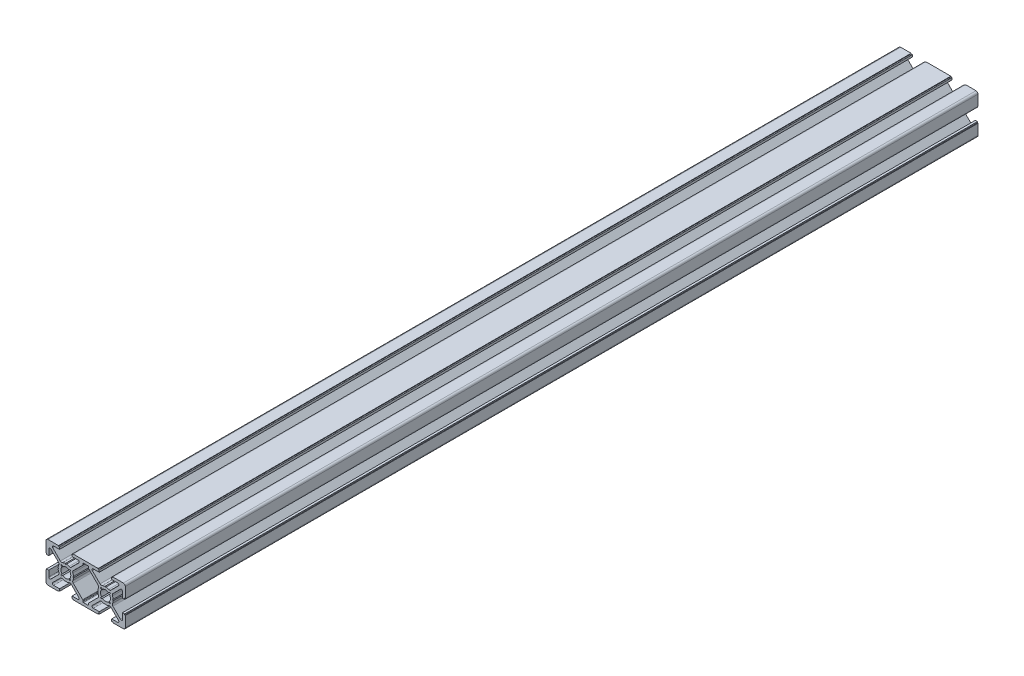
SolidWorks part; units mm, degrees
ref_plane "Front Plane" through (0, 0, 0) normal (0, 0, 1) x (1, 0, 0)
ref_plane "Top Plane" through (0, 0, 0) normal (0, 1, 0) x (1, 0, 0)
ref_plane "Right Plane" through (0, 0, 0) normal (1, 0, 0) x (0, 0, -1)
sketch "Sketch1" plane through (0, 0, 0) normal (0, 0, 1) x (1, 0, 0)
  line B0 (1.9671, 1.5429) -> (2.3335, 1.9092)
  line B1 (1.9092, 2.3335) -> (1.5429, 1.9671)
  line B2 (2.3335, -1.9092) -> (1.9671, -1.5429)
  line B3 (1.5429, -1.9671) -> (1.9092, -2.3335)
  line B4 (-1.9092, -2.3335) -> (-1.5429, -1.9671)
  line B5 (-1.9671, -1.5429) -> (-2.3335, -1.9092)
  line B6 (-2.3335, 1.9092) -> (-1.9671, 1.5429)
  line B7 (-1.5429, 1.9671) -> (-1.9092, 2.3335)
  line B8 (-17.6665, -1.9092) -> (-18.0329, -1.5429)
  line B9 (-18.4571, -1.9671) -> (-18.0908, -2.3335)
  line B10 (-21.9092, -2.3335) -> (-21.5429, -1.9671)
  line B11 (-21.9671, -1.5429) -> (-22.3335, -1.9092)
  line B12 (-18.0329, 1.5429) -> (-17.6665, 1.9092)
  line B13 (-18.0908, 2.3335) -> (-18.4571, 1.9671)
  line B14 (-21.5429, 1.9671) -> (-21.9092, 2.3335)
  line B15 (-22.3335, 1.9092) -> (-21.9671, 1.5429)
  line B16 (-16.1107, 0.2893) -> (-16.4, 0)
  line B17 (-16.4, 0) -> (-16.1107, -0.2893)
  line B18 (-16.2554, -2.7546) -> (-11.4879, -7.5222)
  line B19 (-11.4, -7.7343) -> (-11.4, -8.3)
  line B20 (-11.1, -8.6) -> (-8.9, -8.6)
  line B21 (-8.6, -8.3) -> (-8.6, -7.7343)
  line B22 (-8.5121, -7.5222) -> (-3.7446, -2.7546)
  line B23 (-3.8893, -0.2893) -> (-3.6, 0)
  line B24 (-3.6, 0) -> (-3.8893, 0.2893)
  line B25 (-3.7446, 2.7546) -> (-8.5121, 7.5222)
  line B26 (-8.6, 7.7343) -> (-8.6, 8.3)
  line B27 (-8.9, 8.6) -> (-11.1, 8.6)
  line B28 (-11.4, 8.3) -> (-11.4, 7.7343)
  line B29 (-11.4879, 7.5222) -> (-16.2554, 2.7546)
  line B30 (-30, -3.7) -> (-30, -9)
  line B31 (-29, -10) -> (-23.7, -10)
  line B32 (-23.7, -10) -> (-23.7, -9.7)
  line B33 (-23.7, -9.7) -> (-23.15, -9.7)
  line B34 (-23.15, -9.7) -> (-23.15, -8.6)
  line B35 (-23.15, -8.6) -> (-26.1615, -8.6)
  line B36 (-26.5858, -7.5757) -> (-22.7546, -3.7446)
  line B37 (-20.2893, -3.8893) -> (-20, -3.6)
  line B38 (-20, -3.6) -> (-19.7107, -3.8893)
  line B39 (-17.2454, -3.7446) -> (-13.4142, -7.5757)
  line B40 (-13.8385, -8.6) -> (-16.85, -8.6)
  line B41 (-16.85, -8.6) -> (-16.85, -9.7)
  line B42 (-16.85, -9.7) -> (-16.3, -9.7)
  line B43 (-16.3, -9.7) -> (-16.3, -10)
  line B44 (-16.3, -10) -> (-3.7, -10)
  line B45 (-3.7, -10) -> (-3.7, -9.7)
  line B46 (-3.7, -9.7) -> (-3.15, -9.7)
  line B47 (-3.15, -9.7) -> (-3.15, -8.6)
  line B48 (-3.15, -8.6) -> (-6.1615, -8.6)
  line B49 (-6.5858, -7.5757) -> (-2.7546, -3.7446)
  line B50 (-0.2893, -3.8893) -> (0, -3.6)
  line B51 (0, -3.6) -> (0.2893, -3.8893)
  line B52 (2.7546, -3.7446) -> (6.5858, -7.5757)
  line B53 (6.1615, -8.6) -> (3.15, -8.6)
  line B54 (3.15, -8.6) -> (3.15, -9.7)
  line B55 (3.15, -9.7) -> (3.7, -9.7)
  line B56 (3.7, -9.7) -> (3.7, -10)
  line B57 (3.7, -10) -> (9, -10)
  line B58 (10, -9) -> (10, -3.7)
  line B59 (10, -3.7) -> (9.7, -3.7)
  line B60 (9.7, -3.7) -> (9.7, -3.15)
  line B61 (9.7, -3.15) -> (8.6, -3.15)
  line B62 (8.6, -3.15) -> (8.6, -6.1615)
  line B63 (7.5757, -6.5858) -> (3.7446, -2.7546)
  line B64 (3.8893, -0.2893) -> (3.6, 0)
  line B65 (3.6, 0) -> (3.8893, 0.2893)
  line B66 (3.7446, 2.7546) -> (7.5757, 6.5858)
  line B67 (8.6, 6.1615) -> (8.6, 3.15)
  line B68 (8.6, 3.15) -> (9.7, 3.15)
  line B69 (9.7, 3.15) -> (9.7, 3.7)
  line B70 (9.7, 3.7) -> (10, 3.7)
  line B71 (10, 3.7) -> (10, 9)
  line B72 (9, 10) -> (3.7, 10)
  line B73 (3.7, 10) -> (3.7, 9.7)
  line B74 (3.7, 9.7) -> (3.15, 9.7)
  line B75 (3.15, 9.7) -> (3.15, 8.6)
  line B76 (3.15, 8.6) -> (6.1615, 8.6)
  line B77 (6.5858, 7.5757) -> (2.7546, 3.7446)
  line B78 (0.2893, 3.8893) -> (0, 3.6)
  line B79 (0, 3.6) -> (-0.2893, 3.8893)
  line B80 (-2.7546, 3.7446) -> (-6.5858, 7.5757)
  line B81 (-6.1615, 8.6) -> (-3.15, 8.6)
  line B82 (-3.15, 8.6) -> (-3.15, 9.7)
  line B83 (-3.15, 9.7) -> (-3.7, 9.7)
  line B84 (-3.7, 9.7) -> (-3.7, 10)
  line B85 (-3.7, 10) -> (-16.3, 10)
  line B86 (-16.3, 10) -> (-16.3, 9.7)
  line B87 (-16.3, 9.7) -> (-16.85, 9.7)
  line B88 (-16.85, 9.7) -> (-16.85, 8.6)
  line B89 (-16.85, 8.6) -> (-13.8385, 8.6)
  line B90 (-13.4142, 7.5757) -> (-17.2454, 3.7446)
  line B91 (-19.7107, 3.8893) -> (-20, 3.6)
  line B92 (-20, 3.6) -> (-20.2893, 3.8893)
  line B93 (-22.7546, 3.7446) -> (-26.5858, 7.5757)
  line B94 (-26.1615, 8.6) -> (-23.15, 8.6)
  line B95 (-23.15, 8.6) -> (-23.15, 9.7)
  line B96 (-23.15, 9.7) -> (-23.7, 9.7)
  line B97 (-23.7, 9.7) -> (-23.7, 10)
  line B98 (-23.7, 10) -> (-29, 10)
  line B99 (-30, 9) -> (-30, 3.7)
  line B100 (-30, 3.7) -> (-29.7, 3.7)
  line B101 (-29.7, 3.7) -> (-29.7, 3.15)
  line B102 (-29.7, 3.15) -> (-28.6, 3.15)
  line B103 (-28.6, 3.15) -> (-28.6, 6.1615)
  line B104 (-27.5757, 6.5858) -> (-23.7446, 2.7546)
  line B105 (-23.8893, 0.2893) -> (-23.6, 0)
  line B106 (-23.6, 0) -> (-23.8893, -0.2893)
  line B107 (-23.7446, -2.7546) -> (-27.5757, -6.5858)
  line B108 (-28.6, -6.1615) -> (-28.6, -3.15)
  line B109 (-28.6, -3.15) -> (-29.7, -3.15)
  line B110 (-29.7, -3.15) -> (-29.7, -3.7)
  line B111 (-29.7, -3.7) -> (-30, -3.7)
  arc B112 (1.9671, -1.5429) -> (1.9671, 1.5429) centre (0, 0) ccw
  arc B113 (2.3335, 1.9092) -> (1.9092, 2.3335) centre (2.1213, 2.1213) ccw
  arc B114 (1.5429, 1.9671) -> (-1.5429, 1.9671) centre (0, 0) ccw
  arc B115 (1.9092, -2.3335) -> (2.3335, -1.9092) centre (2.1213, -2.1213) ccw
  arc B116 (-1.5429, -1.9671) -> (1.5429, -1.9671) centre (0, 0) ccw
  arc B117 (-2.3335, -1.9092) -> (-1.9092, -2.3335) centre (-2.1213, -2.1213) ccw
  arc B118 (-1.9671, 1.5429) -> (-1.9671, -1.5429) centre (0, 0) ccw
  arc B119 (-1.9092, 2.3335) -> (-2.3335, 1.9092) centre (-2.1213, 2.1213) ccw
  arc B120 (-18.0908, -2.3335) -> (-17.6665, -1.9092) centre (-17.8787, -2.1213) ccw
  arc B121 (-21.5429, -1.9671) -> (-18.4571, -1.9671) centre (-20, 0) ccw
  arc B122 (-22.3335, -1.9092) -> (-21.9092, -2.3335) centre (-22.1213, -2.1213) ccw
  arc B123 (-21.9671, 1.5429) -> (-21.9671, -1.5429) centre (-20, 0) ccw
  arc B124 (-18.0329, -1.5429) -> (-18.0329, 1.5429) centre (-20, 0) ccw
  arc B125 (-17.6665, 1.9092) -> (-18.0908, 2.3335) centre (-17.8787, 2.1213) ccw
  arc B126 (-18.4571, 1.9671) -> (-21.5429, 1.9671) centre (-20, 0) ccw
  arc B127 (-21.9092, 2.3335) -> (-22.3335, 1.9092) centre (-22.1213, 2.1213) ccw
  arc B128 (-30, -9) -> (-29, -10) centre (-29, -9) ccw
  arc B129 (-26.5858, -7.5757) -> (-26.1615, -8.6) centre (-26.1615, -8) ccw
  arc B130 (-21.6297, -3.5432) -> (-22.7546, -3.7446) centre (-22.0475, -4.4517) ccw
  arc B131 (-21.6297, -3.5432) -> (-20.2893, -3.8893) centre (-20, 0) ccw
  arc B132 (-19.7107, -3.8893) -> (-18.3703, -3.5432) centre (-20, 0) ccw
  arc B133 (-17.2454, -3.7446) -> (-18.3703, -3.5432) centre (-17.9525, -4.4517) ccw
  arc B134 (-13.8385, -8.6) -> (-13.4142, -7.5757) centre (-13.8385, -8) ccw
  arc B135 (-6.5858, -7.5757) -> (-6.1615, -8.6) centre (-6.1615, -8) ccw
  arc B136 (-1.6297, -3.5432) -> (-2.7546, -3.7446) centre (-2.0475, -4.4517) ccw
  arc B137 (-1.6297, -3.5432) -> (-0.2893, -3.8893) centre (0, 0) ccw
  arc B138 (0.2893, -3.8893) -> (1.6297, -3.5432) centre (0, 0) ccw
  arc B139 (2.7546, -3.7446) -> (1.6297, -3.5432) centre (2.0475, -4.4517) ccw
  arc B140 (6.1615, -8.6) -> (6.5858, -7.5757) centre (6.1615, -8) ccw
  arc B141 (9, -10) -> (10, -9) centre (9, -9) ccw
  arc B142 (7.5757, -6.5858) -> (8.6, -6.1615) centre (8, -6.1615) ccw
  arc B143 (3.5432, -1.6297) -> (3.7446, -2.7546) centre (4.4517, -2.0475) ccw
  arc B144 (3.5432, -1.6297) -> (3.8893, -0.2893) centre (0, 0) ccw
  arc B145 (3.8893, 0.2893) -> (3.5432, 1.6297) centre (0, 0) ccw
  arc B146 (3.7446, 2.7546) -> (3.5432, 1.6297) centre (4.4517, 2.0475) ccw
  arc B147 (8.6, 6.1615) -> (7.5757, 6.5858) centre (8, 6.1615) ccw
  arc B148 (10, 9) -> (9, 10) centre (9, 9) ccw
  arc B149 (6.5858, 7.5757) -> (6.1615, 8.6) centre (6.1615, 8) ccw
  arc B150 (1.6297, 3.5432) -> (2.7546, 3.7446) centre (2.0475, 4.4517) ccw
  arc B151 (1.6297, 3.5432) -> (0.2893, 3.8893) centre (0, 0) ccw
  arc B152 (-0.2893, 3.8893) -> (-1.6297, 3.5432) centre (0, 0) ccw
  arc B153 (-2.7546, 3.7446) -> (-1.6297, 3.5432) centre (-2.0475, 4.4517) ccw
  arc B154 (-6.1615, 8.6) -> (-6.5858, 7.5757) centre (-6.1615, 8) ccw
  arc B155 (-13.4142, 7.5757) -> (-13.8385, 8.6) centre (-13.8385, 8) ccw
  arc B156 (-18.3703, 3.5432) -> (-17.2454, 3.7446) centre (-17.9525, 4.4517) ccw
  arc B157 (-18.3703, 3.5432) -> (-19.7107, 3.8893) centre (-20, 0) ccw
  arc B158 (-20.2893, 3.8893) -> (-21.6297, 3.5432) centre (-20, 0) ccw
  arc B159 (-22.7546, 3.7446) -> (-21.6297, 3.5432) centre (-22.0475, 4.4517) ccw
  arc B160 (-26.1615, 8.6) -> (-26.5858, 7.5757) centre (-26.1615, 8) ccw
  arc B161 (-29, 10) -> (-30, 9) centre (-29, 9) ccw
  arc B162 (-27.5757, 6.5858) -> (-28.6, 6.1615) centre (-28, 6.1615) ccw
  arc B163 (-23.5432, 1.6297) -> (-23.7446, 2.7546) centre (-24.4517, 2.0475) ccw
  arc B164 (-23.5432, 1.6297) -> (-23.8893, 0.2893) centre (-20, 0) ccw
  arc B165 (-23.8893, -0.2893) -> (-23.5432, -1.6297) centre (-20, 0) ccw
  arc B166 (-23.7446, -2.7546) -> (-23.5432, -1.6297) centre (-24.4517, -2.0475) ccw
  arc B167 (-28.6, -6.1615) -> (-27.5757, -6.5858) centre (-28, -6.1615) ccw
  arc B168 (-16.4568, -1.6297) -> (-16.1107, -0.2893) centre (-20, 0) ccw
  arc B169 (-16.4568, -1.6297) -> (-16.2554, -2.7546) centre (-15.5483, -2.0475) ccw
  arc B170 (-11.4, -7.7343) -> (-11.4879, -7.5222) centre (-11.7, -7.7343) ccw
  arc B171 (-11.4, -8.3) -> (-11.1, -8.6) centre (-11.1, -8.3) ccw
  arc B172 (-8.9, -8.6) -> (-8.6, -8.3) centre (-8.9, -8.3) ccw
  arc B173 (-8.5121, -7.5222) -> (-8.6, -7.7343) centre (-8.3, -7.7343) ccw
  arc B174 (-3.7446, -2.7546) -> (-3.5432, -1.6297) centre (-4.4517, -2.0475) ccw
  arc B175 (-3.8893, -0.2893) -> (-3.5432, -1.6297) centre (0, 0) ccw
  arc B176 (-3.5432, 1.6297) -> (-3.8893, 0.2893) centre (0, 0) ccw
  arc B177 (-3.5432, 1.6297) -> (-3.7446, 2.7546) centre (-4.4517, 2.0475) ccw
  arc B178 (-8.6, 7.7343) -> (-8.5121, 7.5222) centre (-8.3, 7.7343) ccw
  arc B179 (-8.6, 8.3) -> (-8.9, 8.6) centre (-8.9, 8.3) ccw
  arc B180 (-11.1, 8.6) -> (-11.4, 8.3) centre (-11.1, 8.3) ccw
  arc B181 (-11.4879, 7.5222) -> (-11.4, 7.7343) centre (-11.7, 7.7343) ccw
  arc B182 (-16.2554, 2.7546) -> (-16.4568, 1.6297) centre (-15.5483, 2.0475) ccw
  arc B183 (-16.1107, 0.2893) -> (-16.4568, 1.6297) centre (-20, 0) ccw
sketch_block_instance "Block1-1"
sketch_block "Block1" parameters "D1"=5.3, "D2"=1.1
extrude "Boss-Extrude1" add sketch "Sketch1" along normal blind 430
